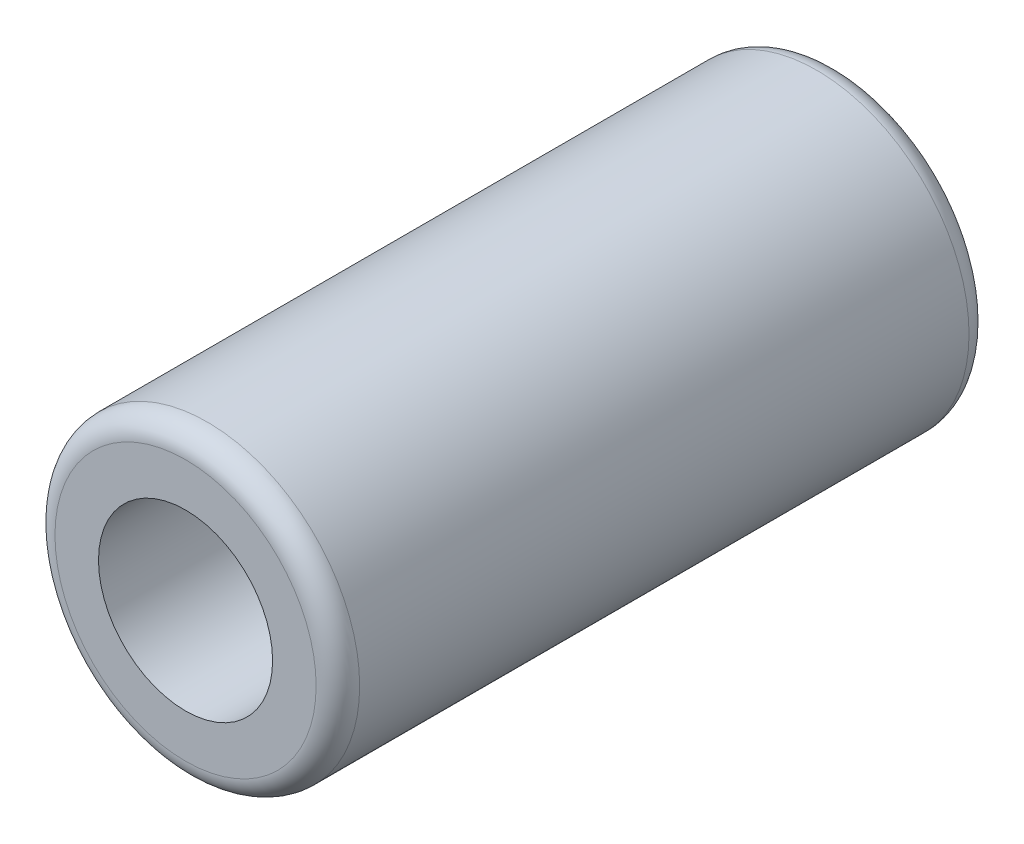
SolidWorks part; units mm, degrees
ref_plane "Front Plane" through (0, 0, 0) normal (0, 0, 1) x (1, 0, 0)
ref_plane "Top Plane" through (0, 0, 0) normal (0, 1, 0) x (1, 0, 0)
ref_plane "Right Plane" through (0, 0, 0) normal (1, 0, 0) x (0, 0, -1)
sketch "Sketch1" plane through (0, 0, 0) normal (0, 0, 1) x (1, 0, 0)
  circle A0 centre (0, 0) radius 2.5
  circle A1 centre (0, 0) radius 7
  dimension "D1" = 5
  dimension "D2" = 14
extrude "Boss-Extrude1" add sketch "Sketch1" along normal blind 30
sketch "Sketch2" plane through (0, 0, 30) normal (0, 0, 1) x (1, 0, 0)
  circle A0 centre (0, 0) radius 4
  dimension "D1" = 8
extrude "Cut-Extrude1" cut sketch "Sketch2" against normal blind 15
fillet "Fillet1" radius 1 2 edges at (7, 0, 0) (7, 0, 30)
